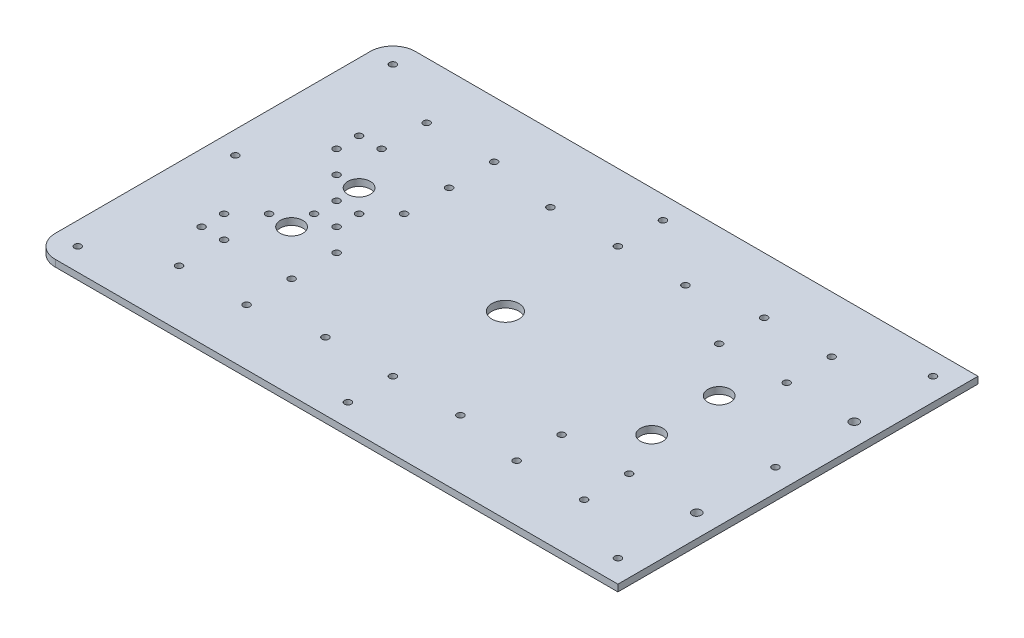
SolidWorks part; units mm, degrees
ref_plane "前视基准面" through (0, 0, 0) normal (0, 0, 1) x (1, 0, 0)
ref_plane "上视基准面" through (0, 0, 0) normal (0, 1, 0) x (1, 0, 0)
ref_plane "右视基准面" through (0, 0, 0) normal (1, 0, 0) x (0, 0, -1)
sketch "草图1" plane through (0, 0, 0) normal (0, 1, 0) x (1, 0, 0)
  line L1 (-130, 80) -> (130, 80)
  line L2 (-130, 80) -> (-130, -80)
  line L3 (-130, -80) -> (130, -80)
  line L4 (130, 80) -> (130, -80)
extrude "凸台-拉伸1" add sketch "草图1" along normal blind 3
sketch "草图2" plane through (0, 3, 0) normal (0, 1, 0) x (1, 0, 0)
  line L0 (130, 80) -> (-130, 80) construction
  line L1 (-130, 80) -> (-130, -80) construction
  circle A0 centre (-90, 55) radius 1.5
  circle A1 centre (-60, 55) radius 1.5
  circle A2 centre (-90, 35) radius 1.5
  circle A3 centre (-60, 35) radius 1.5
  circle A4 centre (-80, 15) radius 5
  dimension "D1" = 30
  dimension "D3" = 20
  dimension "D6" = 20
  dimension "D2" = 25
  dimension "D4" = 20
  dimension "D5" = 40
  dimension "D7" = 0
  dimension "D8" = 0
  dimension "D9" = 10
extrude "切除-拉伸1" cut sketch "草图2" against normal blind 10
mirror "镜向1" about plane through (0, 0, 0) normal (0, 0, 1) of "切除-拉伸1"
mirror "镜向2" about plane through (0, 0, 0) normal (1, 0, 0) of "镜向1", "切除-拉伸1"
sketch "草图3" plane through (0, 3, 0) normal (0, 1, 0) x (1, 0, 0)
  circle A0 centre (0, 0) radius 6
extrude "切除-拉伸2" cut sketch "草图3" against normal blind 10
sketch "草图4" plane through (0, 0, 0) normal (0, -1, 0) x (1, 0, 0)
  circle A0 centre (0, 50) radius 1.5
  circle A1 centre (-30, 50) radius 1.5
  circle A2 centre (30, 50) radius 1.5
extrude "切除-拉伸3" cut sketch "草图4" against normal blind 10
mirror "镜向3" about plane through (0, 0, 0) normal (0, 0, 1) of "切除-拉伸3"
sketch "草图5" plane through (0, 3, 0) normal (0, 1, 0) x (1, 0, 0)
  circle A0 centre (-80, 5) radius 1.5
  circle A1 centre (-70, 5) radius 1.5
  circle A2 centre (-90, 35) radius 1.5 construction
  circle A4 centre (-90, 15) radius 1.5
  circle A5 centre (-60, 15) radius 1.5
  circle A6 centre (-100, 25) radius 1.5
  circle A7 centre (-100, 35) radius 1.5
  dimension "D1" = 10
  dimension "D2" = 30
  dimension "D3" = 10
extrude "切除-拉伸4" cut sketch "草图5" against normal blind 10
mirror "镜向4" about plane through (0, 0, 0) normal (0, 0, 1) of "切除-拉伸4"
fillet "圆角1" radius 10 2 edges at (-130, 1.5, 80) (-130, 1.5, -80)
sketch "草图6" plane through (0, 3, 0) normal (0, 1, 0) x (1, 0, 0)
  circle A0 centre (-120, 70) radius 1.5
  circle A1 centre (0, 70) radius 1.5
  circle A2 centre (120, 70) radius 1.5
extrude "切除-拉伸5" cut sketch "草图6" against normal blind 10
mirror "镜向5" about plane through (0, 0, 0) normal (0, 0, 1) of "切除-拉伸5"
sketch "草图7" plane through (0, 3, 0) normal (0, 1, 0) x (1, 0, 0)
  circle A0 centre (-120, 0) radius 1.5
  circle A1 centre (120, 0) radius 1.5
extrude "切除-拉伸6" cut sketch "草图7" against normal blind 10
sketch "草图8" plane through (0, 0, 0) normal (0, -1, 0) x (-1, 0, 0)
  circle A1 centre (-120, 35) radius 2
  circle A2 centre (-120, -35) radius 2
  circle A3 centre (-120, 0) radius 1.5 construction
  dimension "D1" = 35
  dimension "D2" = 35
extrude "切除-拉伸7" cut sketch "草图8" against normal through all
sketch "草图9" plane through (0, 0, 0) normal (0, -1, 0) x (1, 0, 0)
  line L0 (-130, -70) -> (-130, 70) construction
  line L1 (-57.5, -9.5) -> (-16.5, -9.5)
  line L2 (-57.5, -9.5) -> (-57.5, 11.5)
  line L3 (-57.5, 11.5) -> (-16.5, 11.5)
  line L4 (-16.5, -9.5) -> (-16.5, 11.5)
  line L5 (-120, 80) -> (130, 80) construction
  circle A0 centre (-61.5, -4.5) radius 2
  circle A1 centre (-61.5, 6.5) radius 2
  circle A2 centre (-12.5, -4.5) radius 2
  circle A3 centre (-12.5, 6.5) radius 2
  dimension "D5" = 4
  dimension "D6" = 4
  dimension "D8" = 5
  dimension "D9" = 4
  dimension "D7" = 5
  dimension "D10" = 4
  dimension "D11" = 4
  dimension "D12" = 4
  dimension "D13" = 4
  dimension "D1" = 21
  dimension "D2" = 41
  dimension "D3" = 72.5
  dimension "D4" = 68.5
  dimension "D14" = 4
  dimension "D15" = 5
  dimension "D16" = 5
